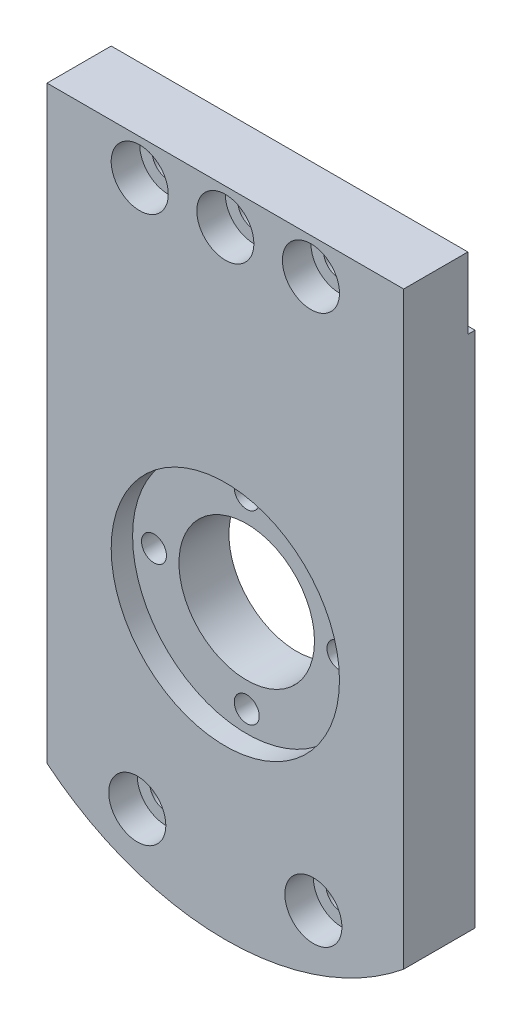
SolidWorks part; units mm, degrees
material "1060 합금"
ref_plane "정면" through (0, 0, 0) normal (0, 0, 1) x (1, 0, 0)
ref_plane "윗면" through (0, 0, 0) normal (0, 1, 0) x (1, 0, 0)
ref_plane "우측면" through (0, 0, 0) normal (1, 0, 0) x (0, 0, -1)
sketch "스케치1" plane through (0, 0, 0) normal (0, 0, 1) x (1, 0, 0)
  line L0 (0, 0) -> (0, 87.6098) construction
  line L1 (-39.5, 0) -> (-39.5, 42) construction
  line L2 (-39.5, 42) -> (39.5, 42) construction
  line L3 (39.5, 42) -> (39.5, 0) construction
  line L4 (-25, 0) -> (-25, 52)
  line L5 (-25, 52) -> (25, 52)
  line L6 (25, 52) -> (25, -30.5819)
  line L7 (-25, 0) -> (-25, -30.5819)
  line L8 (0, 0) -> (0, -39.5) construction
  line L9 (0, 0) -> (-15.116, -36.4932) construction
  line L10 (0, 0) -> (15.116, -36.4932) construction
  line L11 (-25, 47) -> (25, 47) construction
  arc A0 (-39.5, 0) -> (39.5, 0) centre (0, 0) ccw construction
  circle A1 centre (0, 0) radius 25 construction
  circle A2 centre (0, 0) radius 16 construction
  arc A3 (-25, -30.5819) -> (25, -30.5819) centre (0, 0) ccw
  circle A4 centre (0, 0) radius 32.25 construction
  circle A5 centre (-12.3415, -29.7951) radius 2.25
  circle A6 centre (12.3415, -29.7951) radius 2.25
  circle A7 centre (0, 47) radius 2.25
  circle A8 centre (12, 47) radius 2.25
  circle A9 centre (-12, 47) radius 2.25
  circle A10 centre (0, 0) radius 9.5
  circle A11 centre (0, 0) radius 13 construction
  circle A12 centre (-13, 0) radius 1.75
  circle A13 centre (0, 13) radius 1.75
  circle A14 centre (13, 0) radius 1.75
  circle A15 centre (0, -13) radius 1.75
  dimension "D1" = 22.5
  dimension "D2" = 22.5
  dimension "D4" = 4.5
  dimension "D5" = 4.5
  dimension "D6" = 4.5
  dimension "D7" = 4.5
  dimension "D8" = 4.5
  dimension "D11" = 19
  dimension "D12" = 3.5
  dimension "D13" = 3.5
  dimension "D14" = 3.5
  dimension "D15" = 3.5
  dimension "D3" = 5
  dimension "D9" = 12
  dimension "D10" = 12
  dimension "D16" = 52
extrude "보스-돌출1" add sketch "스케치1" along normal blind 10
sketch "스케치3" plane through (0, 0, 10) normal (0, 0, 1) x (1, 0, 0)
  circle A0 centre (0, 0) radius 16
  dimension "D1" = 32
extrude "컷-돌출1" cut sketch "스케치3" against normal blind 3
sketch "스케치4" plane through (0, 0, 10) normal (0, 0, 1) x (1, 0, 0)
  circle A0 centre (-12, 47) radius 4
  circle A1 centre (0, 47) radius 4
  circle A2 centre (12, 47) radius 4
  circle A3 centre (12.3415, -29.7951) radius 4
  circle A4 centre (-12.3415, -29.7951) radius 4
  dimension "D1" = 8
  dimension "D2" = 8
  dimension "D3" = 8
  dimension "D4" = 8
  dimension "D5" = 8
extrude "컷-돌출2" cut sketch "스케치4" against normal blind 4
sketch "스케치5" plane through (0, 0, 0) normal (0, 0, -1) x (-1, 0, 0)
  line L0 (25, 52) -> (25, -30.5819) construction
  line L1 (-25, 52) -> (25, 52)
  line L2 (-25, 52) -> (-25, 42)
  line L3 (-25, 42) -> (25, 42)
  line L4 (25, 52) -> (25, 42)
  dimension "D1" = 10
extrude "컷-돌출3" cut sketch "스케치5" against normal blind 1
sketch "스케치6" plane through (0, 0, 0) normal (0, 0, -1) x (-1, 0, 0)
  circle A0 centre (0, 13) radius 3.25
  circle A1 centre (13, 0) radius 3.25
  circle A2 centre (0, -13) radius 3.25
  circle A3 centre (-13, 0) radius 3.25
  dimension "D1" = 6.5
  dimension "D2" = 6.5
  dimension "D3" = 6.5
  dimension "D4" = 6.5
extrude "컷-돌출4" cut sketch "스케치6" against normal blind 2
